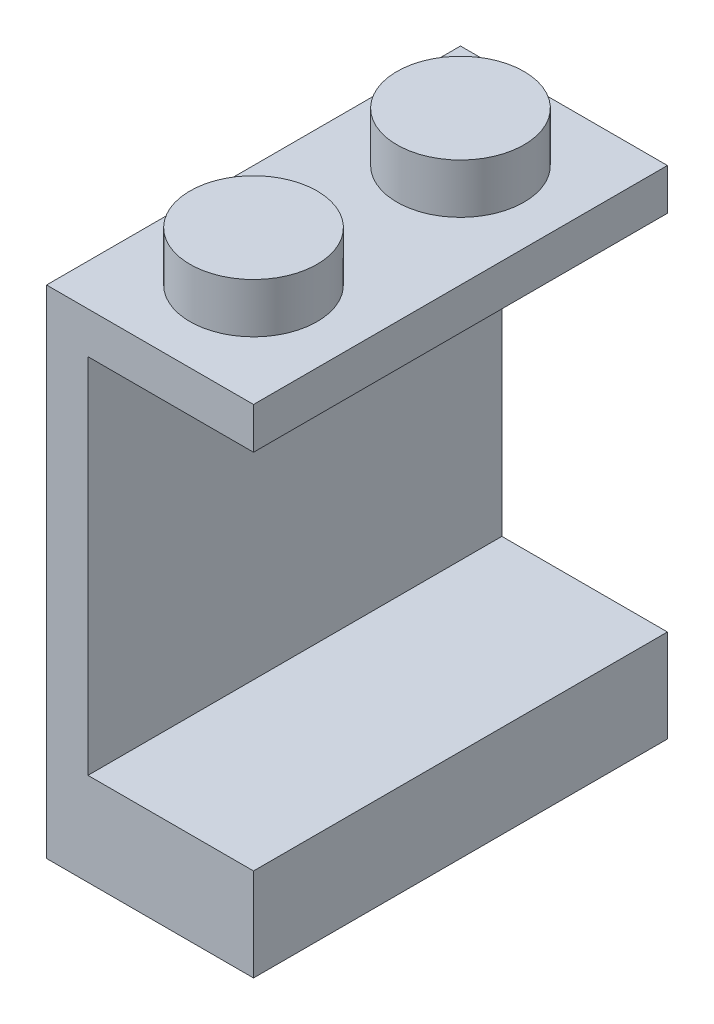
SolidWorks part; units mm, degrees
ref_plane "Front" through (0, 0, 0) normal (0, 0, 1) x (1, 0, 0)
ref_plane "Top" through (0, 0, 0) normal (0, 1, 0) x (1, 0, 0)
ref_plane "Right" through (0, 0, 0) normal (1, 0, 0) x (0, 0, -1)
sketch "Sketch1" plane through (0, 0, 0) normal (0, 1, 0) x (1, 0, 0)
  line L0 (0, 0) -> (0, 50.4571) construction
  line L1 (0, 0) -> (55.8847, 0) construction
  line L2 (-3.9688, 7.9375) -> (3.9688, 7.9375)
  line L3 (-3.9688, 7.9375) -> (-3.9688, -7.9375)
  line L4 (3.9688, -7.9375) -> (-3.9688, -7.9375)
  line L5 (3.9688, -7.9375) -> (3.9688, 7.9375)
  dimension "Length" = 7.9375
  dimension "Width" = 15.875
extrude "Base-Extrude" add sketch "Sketch1" along normal blind 19.05
sketch "Sketch2" plane through (0, 19.05, 0) normal (0, 1, 0) x (-1, 0, 0)
  line L0 (3.9688, -7.9375) -> (3.9688, 7.9375) construction
  line L1 (-3.9688, 7.9375) -> (3.9688, 7.9375) construction
  circle A0 centre (0, 3.9687) radius 2.4384
  dimension "DotDiam" = 4.8768
  dimension "DotLSpc" = 3.9688
  dimension "DotWSpc" = 3.9688
extrude "Boss-Extrude1" add sketch "Sketch2" along normal blind 1.905
pattern_linear "LPattern6" count 2 spacing 7.9375 along (0, 0, -1) of "Boss-Extrude1"
sketch "Sketch4" plane through (0, 0, 0) normal (0, -1, 0) x (1, 0, 0)
  line L4 (-2.3813, 6.35) -> (-2.3813, -6.35)
  line L5 (-2.3813, -6.35) -> (2.3813, -6.35)
  line L6 (2.3813, -6.35) -> (2.3813, 6.35)
  line L7 (2.3813, 6.35) -> (-2.3813, 6.35)
  line L8 (-2.3813, 6.35) -> (-2.3813, -6.35)
  line L9 (-2.3813, -6.35) -> (2.3813, -6.35)
  line L10 (2.3813, -6.35) -> (2.3813, 6.35)
  line L11 (2.3813, 6.35) -> (-2.3813, 6.35)
  dimension "D1" = 1.5875
extrude "Cut-Extrude1" cut sketch "Sketch4" against normal blind 1.5875
sketch "Sketch3" plane through (0, 0, 0) normal (0, -1, 0) x (1, 0, 0)
  line L0 (-3.9688, -7.9375) -> (-3.9688, 7.9375) construction
  circle A0 centre (0, 0) radius 1.27
  dimension "InsDotDiam" = 2.54
  dimension "InsDotSpc" = 3.9688
extrude "InsDot" add sketch "Sketch3" against normal up to next thin
sketch "Sketch5" plane through (0, 0, 7.9375) normal (0, 0, 1) x (1, 0, 0)
  line L0 (3.9688, 17.4625) -> (-2.3813, 17.4625)
  line L1 (3.9688, 17.4625) -> (3.9687, 3.556)
  line L2 (-2.3813, 3.556) -> (3.9687, 3.556)
  line L3 (-2.3813, 3.556) -> (-2.3813, 17.4625)
  line L4 (3.9688, 19.05) -> (3.9688, 0) construction
  line L5 (3.9688, 19.05) -> (-3.9688, 19.05) construction
  line L6 (-3.9688, 19.05) -> (-3.9688, 0) construction
  line L7 (3.9688, 0) -> (-3.9688, 0) construction
  dimension "D1" = 1.5875
  dimension "D2" = 1.5875
  dimension "D3" = 3.556
extrude "Cut-Extrude2" cut sketch "Sketch5" against normal through all
